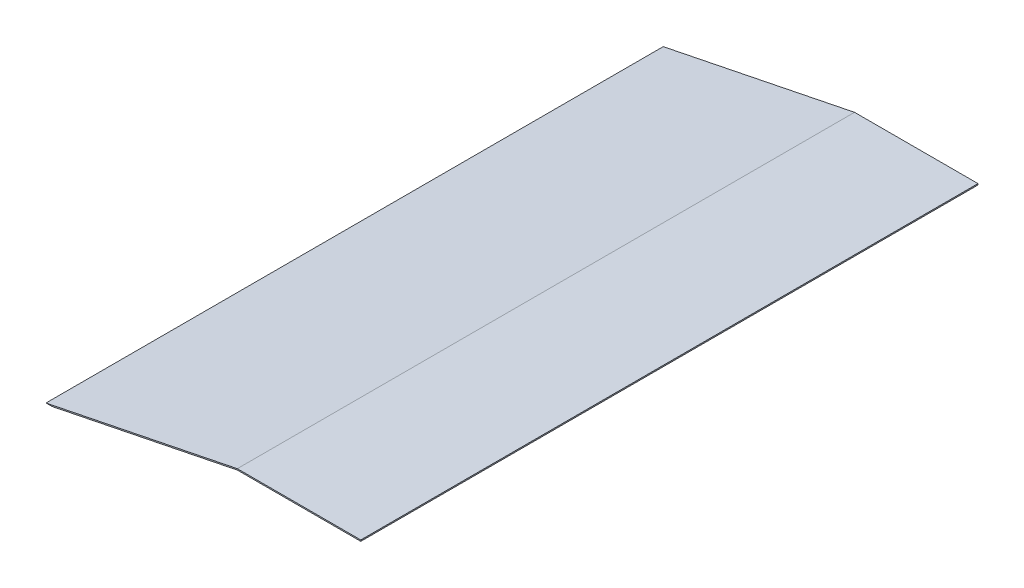
SolidWorks part; units mm, degrees
ref_plane "前视基准面" through (0, 0, 0) normal (0, 0, 1) x (1, 0, 0)
ref_plane "上视基准面" through (0, 0, 0) normal (0, 1, 0) x (1, 0, 0)
ref_plane "右视基准面" through (0, 0, 0) normal (1, 0, 0) x (0, 0, -1)
other "Configuration Table"
sketch "草图1" plane through (0, 0, 0) normal (0, 0, 1) x (1, 0, 0)
  line L0 (0, 0) -> (0, 77.2574) construction
  line L1 (0, 0) -> (-50, 0) construction
  line L2 (-50, 0) -> (-20, 6.0813)
  line L6 (-50, 0) -> (-51, 0)
  line L7 (-51, 0) -> (-20, 6.284)
  line L11 (-20, 6.0813) -> (0, 6.0813)
  line L12 (0, 6.0813) -> (0, 6.284)
  line L13 (0, 6.284) -> (-20, 6.284)
  point P7 (0, 6.284)
  point P17 (0, 6.0813)
  dimension "D1" = 11.459
  dimension "D2" = 30
  dimension "D3" = 20
  dimension "D4" = 1
extrude "凸台-拉伸1" add sketch "草图1" along normal blind 100
